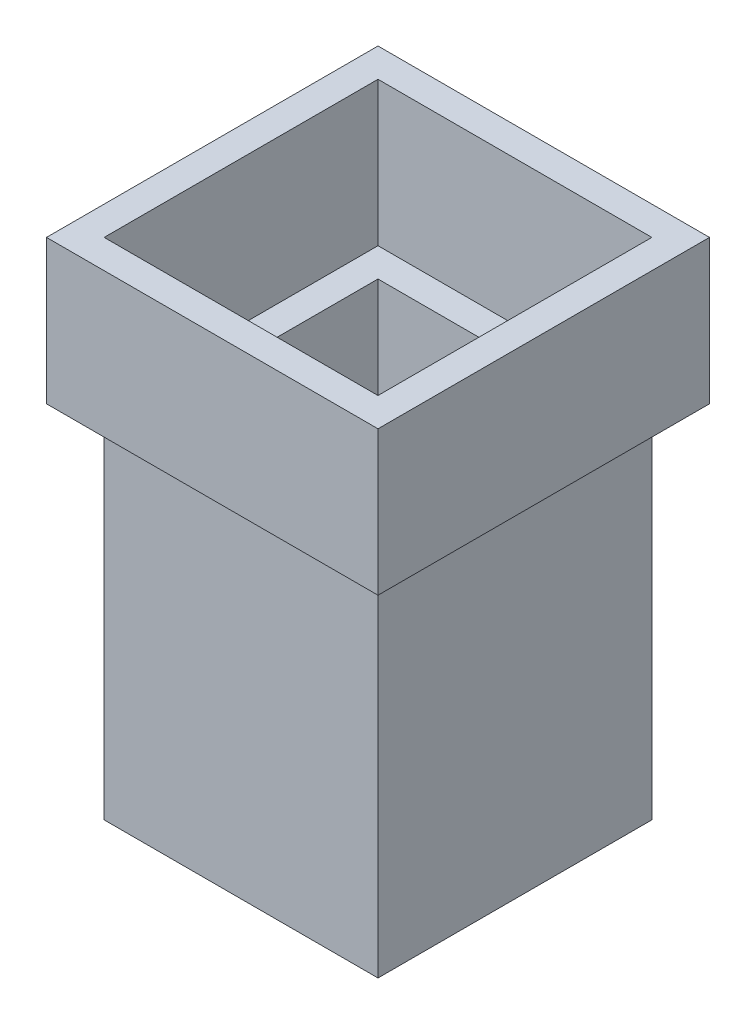
SolidWorks part; units mm, degrees
ref_plane "Alzado" through (0, 0, 0) normal (0, 0, 1) x (1, 0, 0)
ref_plane "Planta" through (0, 0, 0) normal (0, 1, 0) x (1, 0, 0)
ref_plane "Vista lateral" through (0, 0, 0) normal (1, 0, 0) x (0, 0, -1)
sketch "Croquis1" plane through (0, 0, 0) normal (0, 1, 0) x (1, 0, 0)
  line L1 (7.5, 7.5) -> (-7.5, 7.5)
  line L2 (7.5, 7.5) -> (7.5, -7.5)
  line L3 (7.5, -7.5) -> (-7.5, -7.5)
  line L4 (-7.5, 7.5) -> (-7.5, -7.5)
  line L5 (7.5, 7.5) -> (-7.5, -7.5) construction
  line L6 (7.5, -7.5) -> (-7.5, 7.5) construction
  line L7 (9.5, 9.5) -> (-9.5, 9.5)
  line L8 (9.5, 9.5) -> (9.5, -9.5)
  line L9 (9.5, -9.5) -> (-9.5, -9.5)
  line L10 (-9.5, 9.5) -> (-9.5, -9.5)
  line L11 (9.5, 9.5) -> (-9.5, -9.5) construction
  line L12 (9.5, -9.5) -> (-9.5, 9.5) construction
  point P0 (0, 0)
  point P6 (0, 0)
  dimension "D1" = 2
  dimension "D2" = 15
extrude "Saliente-Extruir1" add sketch "Croquis1" along normal blind 25
sketch "Croquis2" plane through (0, 25, 0) normal (0, 1, 0) x (1, 0, 0)
  line L1 (11.5, 11.5) -> (-11.5, 11.5)
  line L2 (11.5, 11.5) -> (11.5, -11.5)
  line L3 (11.5, -11.5) -> (-11.5, -11.5)
  line L4 (-11.5, 11.5) -> (-11.5, -11.5)
  line L5 (11.5, 11.5) -> (-11.5, -11.5) construction
  line L6 (11.5, -11.5) -> (-11.5, 11.5) construction
  line L7 (-9.5, 9.5) -> (9.5, 9.5)
  line L8 (-9.5, 9.5) -> (-9.5, -9.5)
  line L9 (-9.5, -9.5) -> (9.5, -9.5)
  line L10 (9.5, 9.5) -> (9.5, -9.5)
  point P0 (0, 0)
  dimension "D1" = 2
extrude "Saliente-Extruir2" add sketch "Croquis2" along normal blind 10 separate body
